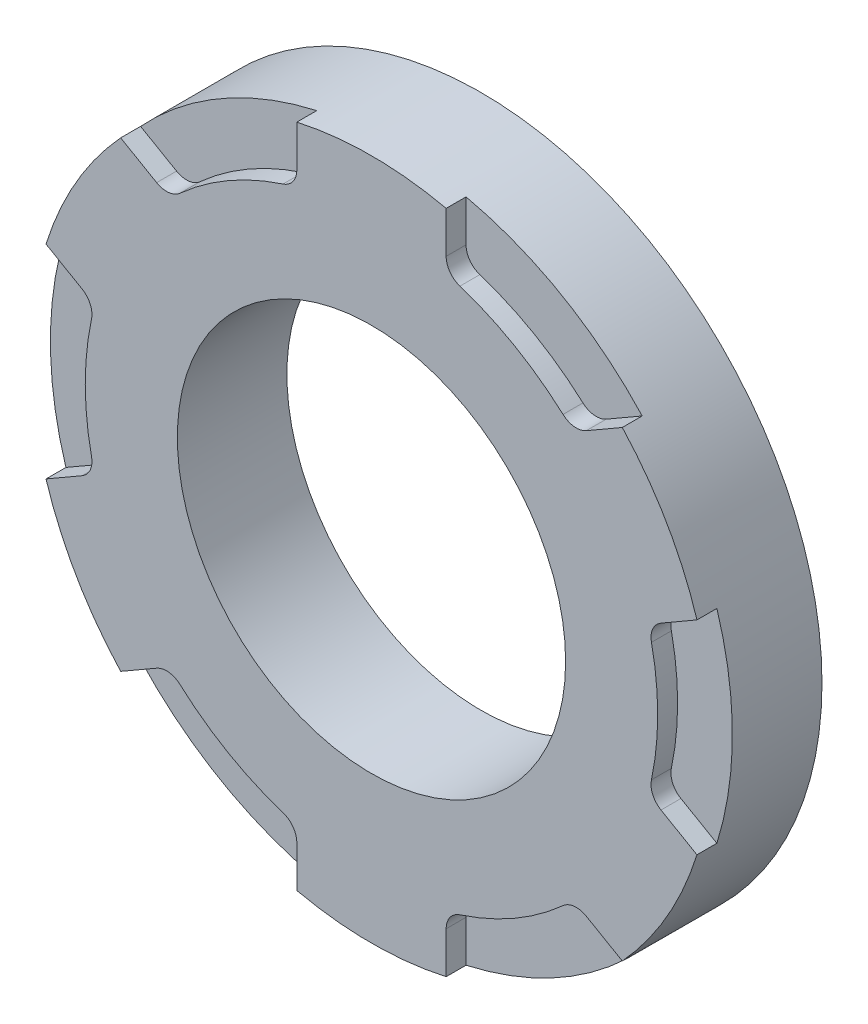
SolidWorks part; units mm, degrees
material "POLYURETHANE (11671)"
ref_plane "Front Plane" through (0, 0, 0) normal (0, 0, 1) x (1, 0, 0)
ref_plane "Top Plane" through (0, 0, 0) normal (0, 1, 0) x (1, 0, 0)
ref_plane "Right Plane" through (0, 0, 0) normal (1, 0, 0) x (0, 0, -1)
sketch "Sketch1" plane through (0, 0, 0) normal (0, 0, 1) x (1, 0, 0)
  circle A0 centre (0, 0) radius 8.6995
  circle A1 centre (0, 0) radius 4.953
  dimension "D1" = 9.906
  dimension "D2" = 17.399
extrude "Boss-Extrude1" add sketch "Sketch1" along normal blind 2.794
ref_plane "Plane1" through (0, 0, 2.794) normal (0, 0, 1) x (1, 0, 0)
sketch "Sketch2" plane through (0, 0, 2.794) normal (0, 0, 1) x (1, 0, 0)
  line L0 (7.3857, 2.0644) -> (8.3036, 2.5944)
  line L1 (8.3036, -2.5944) -> (7.3857, -2.0644)
  line L2 (5.4807, -5.364) -> (6.3986, -5.894)
  line L3 (1.905, -8.4884) -> (1.905, -7.4284)
  line L4 (0, 0) -> (0, 3.5256) construction
  line L5 (0, 0) -> (4.3979, 0) construction
  line L6 (-1.905, -7.4284) -> (-1.905, -8.4884)
  line L7 (-6.3986, -5.894) -> (-5.4807, -5.364)
  line L8 (-7.3857, -2.0644) -> (-8.3036, -2.5944)
  line L9 (-8.3036, 2.5944) -> (-7.3857, 2.0644)
  line L10 (-5.4807, 5.364) -> (-6.3986, 5.894)
  line L11 (6.3986, 5.894) -> (5.4807, 5.364)
  line L12 (-1.905, 8.4884) -> (-1.905, 7.4284)
  line L25 (1.905, 7.4284) -> (1.905, 8.4884)
  arc A0 (7.1428, 1.5188) -> (7.3857, 2.0644) centre (7.6397, 1.6245) cw
  arc A1 (7.1428, -1.5188) -> (7.1428, 1.5188) centre (0, 0) ccw
  arc A2 (7.3857, -2.0644) -> (7.1428, -1.5188) centre (7.6397, -1.6245) cw
  arc A3 (8.3036, -2.5944) -> (8.3036, 2.5944) centre (0, 0) ccw
  arc A4 (4.8867, -5.4264) -> (5.4807, -5.364) centre (5.2267, -5.8039) cw
  arc A5 (2.2561, -6.9453) -> (4.8867, -5.4264) centre (0, 0) ccw
  arc A6 (1.905, -7.4284) -> (2.2561, -6.9453) centre (2.413, -7.4284) cw
  arc A7 (1.905, -8.4884) -> (6.3986, -5.894) centre (0, 0) ccw
  arc A8 (-2.2561, -6.9453) -> (-1.905, -7.4284) centre (-2.413, -7.4284) cw
  arc A9 (-4.8867, -5.4264) -> (-2.2561, -6.9453) centre (0, 0) ccw
  arc A10 (4.8867, 5.4264) -> (2.2561, 6.9453) centre (0, 0) ccw
  arc A11 (6.3986, 5.894) -> (1.905, 8.4884) centre (0, 0) ccw
  arc A12 (-5.4807, -5.364) -> (-4.8867, -5.4264) centre (-5.2267, -5.8039) cw
  arc A13 (-6.3986, -5.894) -> (-1.905, -8.4884) centre (0, 0) ccw
  arc A14 (-7.1428, -1.5188) -> (-7.3857, -2.0644) centre (-7.6397, -1.6245) cw
  arc A15 (-7.1428, 1.5188) -> (-7.1428, -1.5188) centre (0, 0) ccw
  arc A16 (-7.3857, 2.0644) -> (-7.1428, 1.5188) centre (-7.6397, 1.6245) cw
  arc A17 (-8.3036, 2.5944) -> (-8.3036, -2.5944) centre (0, 0) ccw
  arc A18 (-4.8867, 5.4264) -> (-5.4807, 5.364) centre (-5.2267, 5.8039) cw
  arc A19 (-2.2561, 6.9453) -> (-4.8867, 5.4264) centre (0, 0) ccw
  arc A20 (-1.905, 7.4284) -> (-2.2561, 6.9453) centre (-2.413, 7.4284) cw
  arc A21 (5.4807, 5.364) -> (4.8867, 5.4264) centre (5.2267, 5.8039) cw
  arc A22 (2.2561, 6.9453) -> (1.905, 7.4284) centre (2.413, 7.4284) cw
  arc A23 (-1.905, 8.4884) -> (-6.3986, 5.894) centre (0, 0) ccw
  point P52 (5.1527, 5.1746)
  point P55 (1.905, 7.0496)
  dimension "D1" = 7.3025
  dimension "D2" = 8.6995
  dimension "D4" = 0.508
  dimension "D3" = 3.2477
  dimension "D5" = 1.4387
extrude "Cut-Extrude1" cut sketch "Sketch2" against normal blind 0.508
